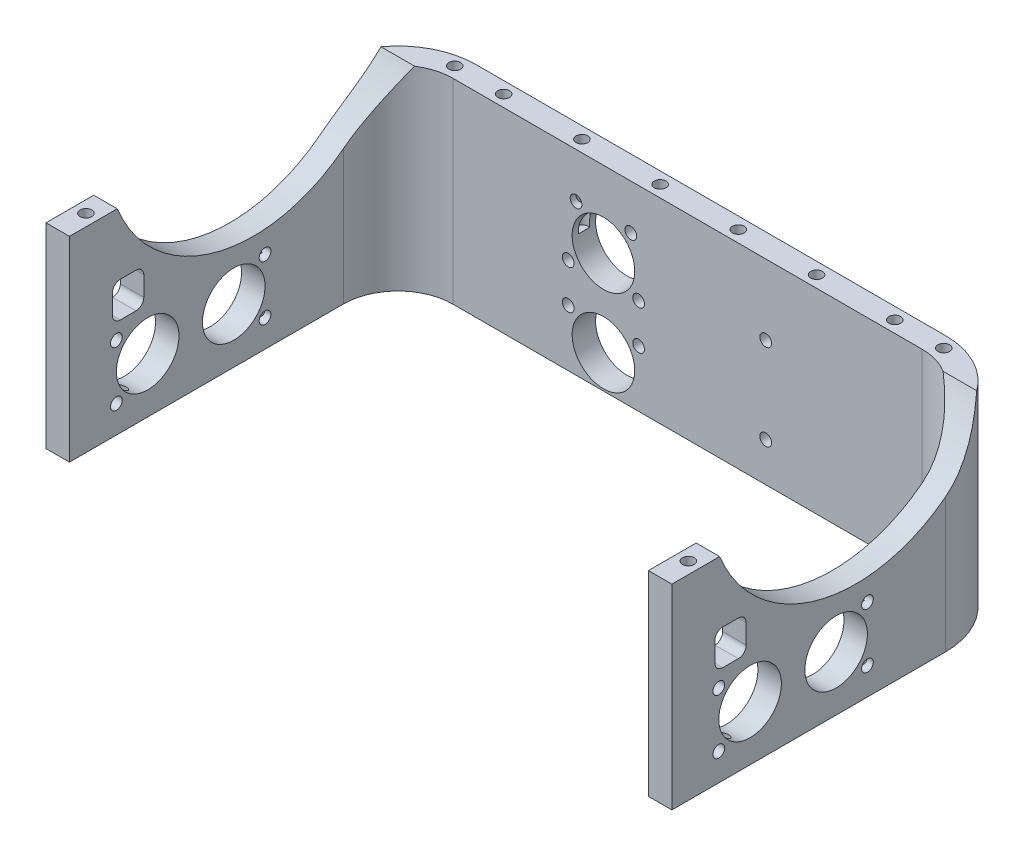
SolidWorks part; units mm, degrees
ref_plane "Alzado" through (0, 0, 0) normal (0, 0, 1) x (1, 0, 0)
ref_plane "Planta" through (0, 0, 0) normal (0, 1, 0) x (1, 0, 0)
ref_plane "Vista lateral" through (0, 0, 0) normal (1, 0, 0) x (0, 0, -1)
sketch "Croquis1" plane through (0, 0, 0) normal (0, 1, 0) x (1, 0, 0)
  line L0 (-20, -6) -> (-140, -6)
  line L1 (-20, 0) -> (-140, 0)
  line L2 (0, -20) -> (0, -90)
  line L3 (0, -90) -> (-6, -90)
  line L4 (-160, -20) -> (-160, -90)
  line L5 (-154, -20) -> (-154, -84)
  line L7 (-6, -20) -> (-6, -84)
  line L8 (-154, -84) -> (-154, -90)
  line L9 (-6, -84) -> (-6, -90)
  line L10 (-154, -90) -> (-160, -90)
  line L11 (-6, -84) -> (-154, -84) construction
  line L12 (0, -90) -> (-160, -90) construction
  arc A0 (-20, 0) -> (0, -20) centre (-20, -20) cw
  arc A1 (-140, 0) -> (-160, -20) centre (-140, -20) ccw
  arc A2 (-140, -6) -> (-154, -20) centre (-140, -20) ccw
  arc A3 (-20, -6) -> (-6, -20) centre (-20, -20) cw
  point P7 (0, 0)
  point P10 (-160, 0)
  dimension "D3" = 20
  dimension "D1" = 160
  dimension "D2" = 90
  dimension "D4" = 6
extrude "Saliente-Extruir1" add sketch "Croquis1" along normal blind 50
sketch "Croquis2" plane through (-160, 0, 0) normal (-1, 0, 0) x (0, 0, 1)
  line L0 (20, 0) -> (90, 0) construction
  line L1 (90, 50) -> (90, 0) construction
  line L2 (29.393, 14) -> (85.5006, 14) construction
  line L3 (59, 30.5874) -> (59, 0) construction
  circle A0 centre (70, 14) radius 8
  circle A1 centre (48, 14) radius 8
  circle A2 centre (40, 21) radius 1.5
  circle A3 centre (40, 7) radius 1.5
  circle A4 centre (78, 21) radius 1.5
  circle A5 centre (78, 7) radius 1.5
  dimension "D1" = 22
  dimension "D2" = 16
  dimension "D5" = 38
  dimension "D7" = 3
  dimension "D3" = 14
  dimension "D4" = 20
  dimension "D6" = 14
extrude "Cortar-Extruir1" cut sketch "Croquis2" against normal blind 173
sketch "Croquis3" plane through (0, 0, 0) normal (1, 0, 0) x (0, 0, -1)
  line L0 (-90, 50) -> (-20, 50) construction
  line L1 (-90, 50) -> (-90, 0) construction
  circle A0 centre (-43, 64) radius 37.5
  dimension "D1" = 14
  dimension "D2" = 75
  dimension "D3" = 47
extrude "Cortar-Extruir2" cut sketch "Croquis3" against normal blind 180
sketch "Croquis4" plane through (0, 0, 0) normal (0, 0, -1) x (-1, 0, 0)
  line L1 (101.5, 48.405) -> (101.5, 3) construction
  line L3 (81.5726, 19.5) -> (129.6143, 19.5) construction
  line L4 (20, 0) -> (140, 0) construction
  line L6 (160, 34.3816) -> (160, 0) construction
  line L13 (20, 50) -> (20, 0) construction
  circle A0 centre (101.5, 8.5) radius 8
  circle A1 centre (101.5, 30.5) radius 8
  circle A2 centre (92.5, 24.5) radius 1.5
  circle A3 centre (92.5, 14.5) radius 1.5
  circle A4 centre (110.5, 24.5) radius 1.5
  circle A5 centre (110.5, 14.5) radius 1.5
  circle A6 centre (108.5, 38.5) radius 1.5
  circle A7 centre (94.5, 38.5) radius 1.5
  circle A11 centre (60, 32) radius 1.5
  circle A12 centre (60, 10) radius 1.5
  dimension "D1" = 22
  dimension "D2" = 16
  dimension "D5" = 10
  dimension "D7" = 3
  dimension "D9" = 3
  dimension "D11" = 22
  dimension "D3" = 19.5
  dimension "D4" = 58.5
  dimension "D6" = 18
  dimension "D8" = 19
  dimension "D10" = 14
  dimension "D12" = 10
  dimension "D13" = 40
extrude "Cortar-Extruir3" cut sketch "Croquis4" against normal blind 10
sketch "Croquis5" plane through (0, 50, 0) normal (0, 1, 0) x (1, 0, 0)
  line L0 (-80, 7.0169) -> (-80, -93.7098) construction
  line L1 (-6, -20) -> (-6, -77.7886) construction
  line L2 (-154, -77.7886) -> (-154, -20) construction
  line L3 (-20, 0) -> (-140, 0) construction
  line L4 (-160, -77.7886) -> (-160, -90) construction
  line L5 (-160, -77.7886) -> (-154, -77.7886) construction
  circle A0 centre (-90, -3) radius 1.5
  circle A1 centre (-110, -3) radius 1.5
  circle A2 centre (-130, -3) radius 1.5
  circle A4 centre (-70, -3) radius 1.5
  circle A5 centre (-50, -3) radius 1.5
  circle A6 centre (-30, -3) radius 1.5
  circle A8 centre (-157, -82.7886) radius 1.5
  circle A9 centre (-3, -82.7886) radius 1.5
  circle A10 centre (-142.5, -3) radius 1.5
  circle A11 centre (-17.5, -3) radius 1.5
  dimension "D1" = 20
  dimension "D5" = 3
  dimension "D4" = 3
  dimension "D9" = 125
  dimension "D2" = 60
  dimension "D3" = 100
  dimension "D6" = 3
  dimension "D7" = 3
  dimension "D8" = 5
extrude "Cortar-Extruir4" cut sketch "Croquis5" against normal blind 20
sketch "Croquis6" plane through (0, 0, 0) normal (0, -1, 0) x (-1, 0, 0)
  line L0 (80, -93.1905) -> (80, 22.0392) construction
  line L1 (6, -20) -> (6, -90) construction
  line L2 (154, -90) -> (154, -20) construction
  line L3 (20, 0) -> (140, 0) construction
  circle A0 centre (88, -3) radius 1.5
  circle A1 centre (115, -3) radius 1.5
  circle A2 centre (130, -3) radius 1.5
  circle A3 centre (72, -3) radius 1.5
  circle A4 centre (45, -3) radius 1.5
  circle A5 centre (30, -3) radius 1.5
  circle A6 centre (157, -38) radius 1.5
  circle A7 centre (157, -74) radius 1.5
  circle A8 centre (3, -74) radius 1.5
  circle A9 centre (3, -38) radius 1.5
  dimension "D1" = 3
  dimension "D2" = 16
  dimension "D3" = 70
  dimension "D4" = 100
  dimension "D5" = 38
  dimension "D6" = 74
  dimension "D7" = 3
  dimension "D8" = 3
extrude "Cortar-Extruir5" cut sketch "Croquis6" against normal blind 20
sketch "Croquis7" plane through (0, 0, 0) normal (1, 0, 0) x (0, 0, -1)
  line L0 (-90, 50) -> (-90, 0) construction
  line L1 (-73, 25) -> (-77, 25)
  line L2 (-71, 27) -> (-71, 32)
  line L3 (-73, 34) -> (-77, 34)
  line L4 (-79, 27) -> (-79, 32)
  line L5 (-90, 50) -> (-77.7886, 50) construction
  arc A0 (-77, 25) -> (-79, 27) centre (-77, 27) cw
  arc A1 (-73, 25) -> (-71, 27) centre (-73, 27) ccw
  arc A2 (-77, 34) -> (-79, 32) centre (-77, 32) ccw
  arc A3 (-71, 32) -> (-73, 34) centre (-73, 32) ccw
  point P11 (-79, 25)
  point P16 (-79, 34)
  point P19 (-71, 34)
  dimension "D5" = 2
  dimension "D6" = 2
  dimension "D7" = 2
  dimension "D1" = 8
  dimension "D2" = 9
  dimension "D3" = 11
  dimension "D4" = 16
extrude "Cortar-Extruir6" cut sketch "Croquis7" against normal blind 210
